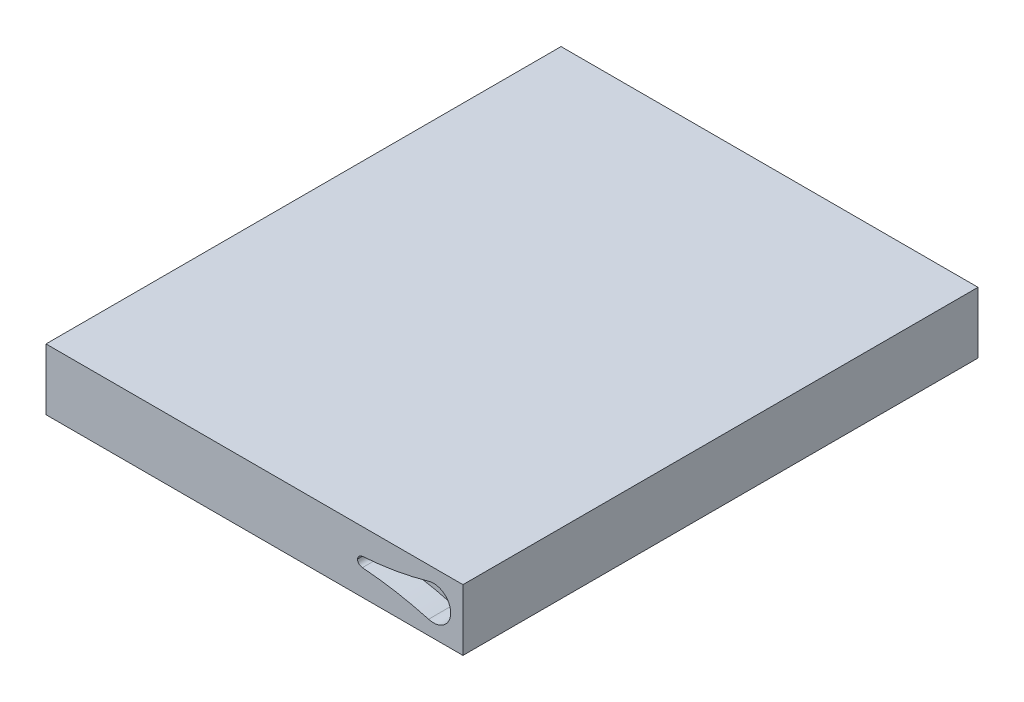
SolidWorks part; units mm, degrees
ref_plane "Front Plane" through (0, 0, 0) normal (0, 0, 1) x (1, 0, 0)
ref_plane "Top Plane" through (0, 0, 0) normal (0, 1, 0) x (1, 0, 0)
ref_plane "Right Plane" through (0, 0, 0) normal (1, 0, 0) x (0, 0, -1)
sketch "Sketch1" plane through (0, 0, 0) normal (0, 1, 0) x (1, 0, 0)
  line L1 (0, 0) -> (80, 0)
  line L2 (0, 0) -> (0, 105)
  line L3 (0, 105) -> (80, 105)
  line L4 (80, 0) -> (80, 105)
  line L5 (80, 105) -> (-5, 105)
  line L6 (80, 105) -> (80, 0)
  line L7 (80, 0) -> (-5, 0)
  line L8 (-5, 105) -> (-5, 0)
  dimension "D1" = 105
  dimension "D2" = 80
  dimension "D3" = 85
extrude "Boss-Extrude1" add sketch "Sketch1" along normal blind 12.5 contours L2 L1 L4 L3 | L6 L5 L8 L7
sketch "Sketch2" plane through (0, 0, 0) normal (0, 0, 1) x (1, 0, 0)
  line L0 (80, 6.25) -> (74, 6.25)
  line L1 (80, 12.5) -> (80, 0) construction
  line L2 (80, 12.5) -> (73, 12.5)
  line L3 (-5, 12.5) -> (80, 12.5) construction
  line L4 (73, 12.5) -> (73, 9.6041)
  line L5 (73, 9.6041) -> (73, 2.8959)
  line L6 (77.5, 6.25) -> (58.5, 6.25)
  line L7 (58.5, 6.25) -> (59.5, 6.25)
  circle A0 centre (74, 6.25) radius 3.5
  arc A1 (58.5, 6.25) -> (59.5, 7.25) centre (59.574, 6.176) cw
  arc A2 (58.5, 6.25) -> (59.5, 5.25) centre (59.5813, 6.3313) ccw
  arc A3 (59.5, 5.25) -> (73, 2.8959) centre (54.2313, -64.8501) cw
  arc A4 (59.5, 7.25) -> (73, 9.6041) centre (54.956, 73.1943) ccw
  dimension "D1" = 7
  dimension "D2" = 7
  dimension "D3" = 19
  dimension "D4" = 1
  dimension "D5" = 1
  dimension "D6" = 1
  dimension "D7" = 6
extrude "Cut-Extrude1" cut sketch "Sketch2" against normal blind 5 contours L0 A0 L5 L6 | L5 A0 L0 L6 | L6 A0 L5 | L5 A0 L6 | A2 A3 A0 L6 | A4 A1 L6 A0
sketch "Sketch5" plane through (0, 0, 0) normal (1, 0, 0) x (0, 0, -1)
  line L0 (0, 12.5) -> (114.4818, 12.5) construction
ref_plane "Plane1" through (0, 0, -105) normal (0, 0, 1) x (1, 0, 0)
